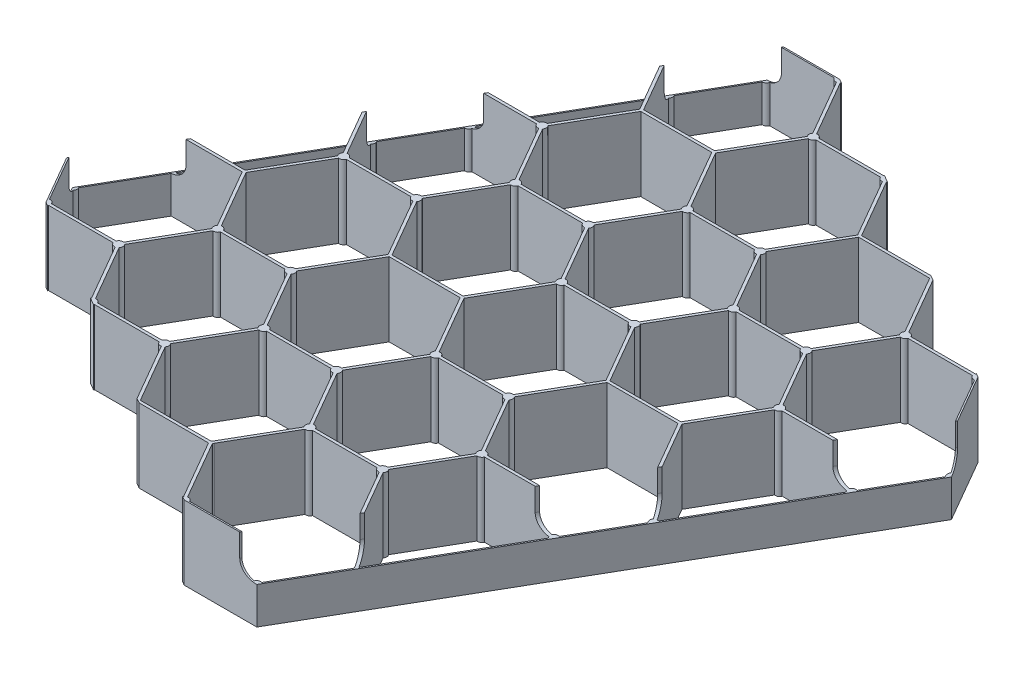
SolidWorks part; units mm, degrees
ref_plane "Front Plane" through (0, 0, 0) normal (0, 0, 1) x (1, 0, 0)
ref_plane "Top Plane" through (0, 0, 0) normal (0, 1, 0) x (1, 0, 0)
ref_plane "Right Plane" through (0, 0, 0) normal (1, 0, 0) x (0, 0, -1)
sketch "Sketch2" plane through (0, 0, 0) normal (0, 1, 0) x (1, 0, 0)
  line L120 (178.2915, 45.6003) -> (166.2528, 66.4519)
  line L121 (167.0028, 23.4497) -> (178.2915, 43.0022)
  line L122 (178.2915, 1.299) -> (167.0028, 20.8516)
  line L124 (166.2528, -22.1506) -> (178.2915, -1.299)
  line L127 (-12.7887, -22.1506) -> (166.2528, -22.1506)
  line L128 (164.8386, 21.6506) -> (142.0896, 21.6506)
  line L130 (177.9013, 0.9747) -> (166.5269, 20.6759)
  line L132 (165.9641, -21.6506) -> (177.9013, -0.9747)
  line L136 (140.9641, -21.6506) -> (165.9641, -21.6506)
  line L139 (129.0269, -0.9747) -> (140.9641, -21.6506)
  line L145 (140.4013, 20.6759) -> (129.0269, 0.9747)
  line L146 (142.0896, 22.6506) -> (164.8386, 22.6506)
  line L147 (129.0269, 43.3265) -> (140.4013, 23.6254)
  line L148 (140.9641, 65.9519) -> (129.0269, 45.276)
  line L149 (165.9641, 65.9519) -> (140.9641, 65.9519)
  line L150 (177.9013, 45.276) -> (165.9641, 65.9519)
  line L154 (178.2915, 87.3035) -> (166.2528, 66.4519)
  line L155 (101.1693, 87.6278) -> (89.2321, 66.9519)
  line L156 (89.7948, 109.2784) -> (101.1693, 89.5773)
  line L157 (65.3576, 110.2532) -> (88.1065, 110.2532)
  line L158 (52.2948, 89.5773) -> (63.6693, 109.2784)
  line L159 (63.9368, 67.4633) -> (52.2948, 87.6278)
  line L160 (89.2321, 66.9519) -> (64.2321, 66.9519)
  line L162 (102.0353, 87.1278) -> (90.3868, 66.9519)
  line L163 (126.4725, 88.1025) -> (103.7236, 88.1025)
  line L164 (139.8094, 66.9519) -> (128.1608, 87.1278)
  line L165 (167.0028, 109.4541) -> (178.2915, 89.9016)
  line L166 (177.9013, 87.6278) -> (165.9641, 66.9519)
  line L167 (166.5269, 109.2784) -> (177.9013, 89.5773)
  line L168 (142.0896, 110.2532) -> (164.8386, 110.2532)
  line L169 (129.0269, 89.5773) -> (140.4013, 109.2784)
  line L170 (140.9641, 66.9519) -> (129.0269, 87.6278)
  line L171 (165.9641, 66.9519) -> (140.9641, 66.9519)
  line L172 (178.2915, 131.6048) -> (167.0028, 112.0522)
  line L173 (166.2528, 155.0544) -> (178.2915, 134.2028)
  line L174 (90.6608, 109.7784) -> (102.0353, 90.0773)
  line L177 (139.5353, 111.7279) -> (128.1608, 131.4291)
  line L178 (128.1608, 90.0773) -> (139.5353, 109.7784)
  line L179 (103.7236, 89.1025) -> (126.4725, 89.1025)
  line L180 (140.9641, 154.5544) -> (165.9641, 154.5544)
  line L181 (129.0269, 133.8786) -> (140.9641, 154.5544)
  line L182 (140.4013, 112.2279) -> (129.0269, 131.9291)
  line L183 (164.8386, 111.2532) -> (142.0896, 111.2532)
  line L184 (177.9013, 131.9291) -> (166.5269, 112.2279)
  line L185 (165.9641, 154.5544) -> (177.9013, 133.8786)
  line L187 (90.0981, 155.0544) -> (102.0353, 134.3786)
  line L189 (128.1608, 134.3786) -> (140.0981, 155.0544)
  line L190 (64.2321, 154.5544) -> (89.2321, 154.5544)
  line L191 (52.2948, 133.8786) -> (64.2321, 154.5544)
  line L192 (63.6693, 112.2279) -> (52.2948, 131.9291)
  line L193 (88.1065, 111.2532) -> (65.3576, 111.2532)
  line L194 (101.1693, 131.9291) -> (89.7948, 112.2279)
  line L195 (89.2321, 154.5544) -> (101.1693, 133.8786)
  line L198 (51.4288, 134.3786) -> (63.366, 155.0544)
  line L199 (26.9916, 133.4038) -> (49.7405, 133.4038)
  line L200 (13.366, 155.0544) -> (25.3033, 134.3786)
  line L203 (-13.0628, 112.2279) -> (-24.4372, 131.9291)
  line L204 (11.3745, 111.2532) -> (-11.3745, 111.2532)
  line L205 (24.4372, 131.9291) -> (13.0628, 112.2279)
  line L206 (12.5, 154.5544) -> (24.4372, 133.8786)
  line L207 (-12.5, 154.5544) -> (12.5, 154.5544)
  line L208 (-24.4372, 133.8786) -> (-12.5, 154.5544)
  line L209 (13.9288, 109.7784) -> (25.3033, 90.0773)
  line L210 (25.3033, 131.4291) -> (13.9288, 111.7279)
  line L211 (49.7405, 132.4038) -> (26.9916, 132.4038)
  line L212 (62.8033, 111.7279) -> (51.4288, 131.4291)
  line L213 (51.4288, 90.0773) -> (62.8033, 109.7784)
  line L214 (26.9916, 89.1025) -> (49.7405, 89.1025)
  line L216 (51.4288, 87.1278) -> (63.0774, 66.9519)
  line L217 (26.9916, 88.1025) -> (49.7405, 88.1025)
  line L218 (13.6547, 66.9519) -> (25.3033, 87.1278)
  line L220 (-13.0628, 109.2784) -> (-24.4372, 89.5773)
  line L221 (11.3745, 110.2532) -> (-11.3745, 110.2532)
  line L222 (24.4372, 89.5773) -> (13.0628, 109.2784)
  line L223 (12.5, 66.9519) -> (24.4372, 87.6278)
  line L224 (-12.5, 66.9519) -> (12.5, 66.9519)
  line L225 (-24.4372, 87.6278) -> (-12.5, 66.9519)
  line L228 (166.5269, 23.6254) -> (177.9013, 43.3265)
  line L255 (-13.0628, 289.433) -> (-24.4372, 309.1341)
  line L257 (139.8094, 65.9519) -> (128.1608, 45.776)
  line L259 (102.0353, 45.776) -> (90.3868, 65.9519)
  line L260 (126.4725, 44.8013) -> (103.7236, 44.8013)
  line L261 (13.6547, 65.9519) -> (25.3033, 45.776)
  line L263 (51.4288, 45.776) -> (63.0774, 65.9519)
  line L264 (26.9916, 44.8013) -> (49.7405, 44.8013)
  line L265 (12.5, 65.9519) -> (24.4372, 45.276)
  line L266 (-12.5, 65.9519) -> (12.5, 65.9519)
  line L267 (-24.4372, 45.276) -> (-12.5, 65.9519)
  line L268 (-13.0628, 23.6254) -> (-24.4372, 43.3265)
  line L269 (11.3745, 22.6506) -> (-11.3745, 22.6506)
  line L270 (24.4372, 43.3265) -> (13.0628, 23.6254)
  line L271 (90.3868, -21.6506) -> (102.0353, -1.4747)
  line L272 (90.3868, -21.6506) -> (139.8094, -21.6506)
  line L273 (128.1608, -1.4747) -> (139.8094, -21.6506)
  line L274 (103.7236, -0.5) -> (126.4725, -0.5)
  line L275 (103.7236, 43.8013) -> (126.4725, 43.8013)
  line L276 (90.6608, 23.1254) -> (102.0353, 42.8265)
  line L277 (102.0353, 1.4747) -> (90.6608, 21.1759)
  line L278 (126.4725, 0.5) -> (103.7236, 0.5)
  line L279 (139.5353, 21.1759) -> (128.1608, 1.4747)
  line L280 (128.1608, 42.8265) -> (139.5353, 23.1254)
  line L281 (65.3576, 22.6506) -> (88.1065, 22.6506)
  line L282 (52.2948, 43.3265) -> (63.6693, 23.6254)
  line L283 (64.2321, 65.9519) -> (52.2948, 45.276)
  line L284 (89.2321, 65.9519) -> (64.2321, 65.9519)
  line L285 (101.1693, 45.276) -> (89.2321, 65.9519)
  line L286 (89.7948, 23.6254) -> (101.1693, 43.3265)
  line L287 (88.1065, 21.6506) -> (65.3576, 21.6506)
  line L288 (101.1693, 0.9747) -> (89.7948, 20.6759)
  line L289 (89.2321, -21.6506) -> (101.1693, -0.9747)
  line L290 (64.2321, -21.6506) -> (89.2321, -21.6506)
  line L291 (52.2948, -0.9747) -> (64.2321, -21.6506)
  line L292 (63.6693, 20.6759) -> (52.2948, 0.9747)
  line L293 (13.9288, 23.1254) -> (25.3033, 42.8265)
  line L294 (25.3033, 1.4747) -> (13.9288, 21.1759)
  line L295 (49.7405, 0.5) -> (26.9916, 0.5)
  line L296 (62.8033, 21.1759) -> (51.4288, 1.4747)
  line L297 (51.4288, 42.8265) -> (62.8033, 23.1254)
  line L298 (26.9916, 43.8013) -> (49.7405, 43.8013)
  line L299 (13.6547, -21.6506) -> (25.3033, -1.4747)
  line L300 (13.6547, -21.6506) -> (63.0774, -21.6506)
  line L301 (51.4288, -1.4747) -> (63.0774, -21.6506)
  line L302 (26.9916, -0.5) -> (49.7405, -0.5)
  line L303 (11.3745, 21.6506) -> (-11.3745, 21.6506)
  line L304 (24.4372, 0.9747) -> (13.0628, 20.6759)
  line L305 (12.5, -21.6506) -> (24.4372, -0.9747)
  line L306 (-12.5, -21.6506) -> (12.5, -21.6506)
  line L307 (-24.4372, -0.9747) -> (-12.5, -21.6506)
  line L308 (-13.0628, 20.6759) -> (-24.4372, 0.9747)
  line L309 (-24.4372, 311.0836) -> (-12.5, 331.7595)
  line L310 (-12.5, 331.7595) -> (12.5, 331.7595)
  line L311 (12.5, 331.7595) -> (24.4372, 311.0836)
  line L312 (24.4372, 309.1341) -> (13.0628, 289.433)
  line L313 (11.3745, 288.4583) -> (-11.3745, 288.4583)
  line L314 (26.9916, 310.6089) -> (49.7405, 310.6089)
  line L315 (51.4288, 311.5836) -> (63.0774, 331.7595)
  line L316 (13.6547, 331.7595) -> (63.0774, 331.7595)
  line L317 (13.6547, 331.7595) -> (25.3033, 311.5836)
  line L318 (26.9916, 266.3076) -> (49.7405, 266.3076)
  line L319 (51.4288, 267.2824) -> (62.8033, 286.9835)
  line L320 (62.8033, 288.933) -> (51.4288, 308.6341)
  line L321 (49.7405, 309.6089) -> (26.9916, 309.6089)
  line L322 (25.3033, 308.6341) -> (13.9288, 288.933)
  line L323 (13.9288, 286.9835) -> (25.3033, 267.2824)
  line L324 (63.6693, 289.433) -> (52.2948, 309.1341)
  line L325 (52.2948, 311.0836) -> (64.2321, 331.7595)
  line L326 (64.2321, 331.7595) -> (89.2321, 331.7595)
  line L327 (89.2321, 331.7595) -> (101.1693, 311.0836)
  line L328 (101.1693, 309.1341) -> (89.7948, 289.433)
  line L329 (88.1065, 288.4583) -> (65.3576, 288.4583)
  line L330 (89.7948, 286.4835) -> (101.1693, 266.7824)
  line L331 (101.1693, 264.8329) -> (89.2321, 244.157)
  line L332 (89.2321, 244.157) -> (64.2321, 244.157)
  line L333 (64.2321, 244.157) -> (52.2948, 264.8329)
  line L334 (52.2948, 266.7824) -> (63.6693, 286.4835)
  line L335 (65.3576, 287.4583) -> (88.1065, 287.4583)
  line L336 (128.1608, 267.2824) -> (139.5353, 286.9835)
  line L337 (139.5353, 288.933) -> (128.1608, 308.6341)
  line L338 (126.4725, 309.6089) -> (103.7236, 309.6089)
  line L339 (102.0353, 308.6341) -> (90.6608, 288.933)
  line L340 (90.6608, 286.9835) -> (102.0353, 267.2824)
  line L341 (103.7236, 266.3076) -> (126.4725, 266.3076)
  line L342 (103.7236, 310.6089) -> (126.4725, 310.6089)
  line L343 (128.1608, 311.5836) -> (139.8094, 331.7595)
  line L344 (90.3868, 331.7595) -> (139.8094, 331.7595)
  line L345 (90.3868, 331.7595) -> (102.0353, 311.5836)
  line L346 (24.4372, 266.7824) -> (13.0628, 286.4835)
  line L347 (11.3745, 287.4583) -> (-11.3745, 287.4583)
  line L348 (-13.0628, 286.4835) -> (-24.4372, 266.7824)
  line L349 (-24.4372, 264.8329) -> (-12.5, 244.157)
  line L350 (-12.5, 244.157) -> (12.5, 244.157)
  line L351 (12.5, 244.157) -> (24.4372, 264.8329)
  line L352 (26.9916, 265.3076) -> (49.7405, 265.3076)
  line L353 (51.4288, 264.3329) -> (63.366, 243.657)
  line L355 (13.366, 243.657) -> (25.3033, 264.3329)
  line L356 (126.4725, 265.3076) -> (103.7236, 265.3076)
  line L357 (102.0353, 264.3329) -> (90.0981, 243.657)
  line L359 (140.0981, 243.657) -> (128.1608, 264.3329)
  line L360 (166.5269, 286.4835) -> (177.9013, 266.7824)
  line L362 (-24.4372, 222.4811) -> (-12.5, 243.157)
  line L363 (-12.5, 243.157) -> (12.5, 243.157)
  line L364 (12.5, 243.157) -> (24.4372, 222.4811)
  line L365 (24.4372, 220.5316) -> (13.0628, 200.8305)
  line L366 (11.3745, 199.8557) -> (-11.3745, 199.8557)
  line L367 (-13.0628, 200.8305) -> (-24.4372, 220.5316)
  line L369 (13.366, 243.657) -> (25.3033, 222.9811)
  line L370 (26.9916, 222.0064) -> (49.7405, 222.0064)
  line L371 (51.4288, 222.9811) -> (63.366, 243.657)
  line L373 (26.9916, 221.0064) -> (49.7405, 221.0064)
  line L374 (51.4288, 220.0316) -> (62.8033, 200.3305)
  line L375 (62.8033, 198.381) -> (51.4288, 178.6798)
  line L376 (49.7405, 177.7051) -> (26.9916, 177.7051)
  line L377 (25.3033, 178.6798) -> (13.9288, 198.381)
  line L378 (13.9288, 200.3305) -> (25.3033, 220.0316)
  line L379 (-24.4372, 176.2303) -> (-12.5, 155.5544)
  line L380 (-12.5, 155.5544) -> (12.5, 155.5544)
  line L381 (12.5, 155.5544) -> (24.4372, 176.2303)
  line L382 (24.4372, 178.1798) -> (13.0628, 197.881)
  line L383 (11.3745, 198.8557) -> (-11.3745, 198.8557)
  line L384 (-13.0628, 197.881) -> (-24.4372, 178.1798)
  line L387 (13.366, 155.0544) -> (25.3033, 175.7303)
  line L388 (26.9916, 176.7051) -> (49.7405, 176.7051)
  line L389 (51.4288, 175.7303) -> (63.366, 155.0544)
  line L391 (89.2321, 155.5544) -> (101.1693, 176.2303)
  line L392 (101.1693, 178.1798) -> (89.7948, 197.881)
  line L393 (88.1065, 198.8557) -> (65.3576, 198.8557)
  line L394 (63.6693, 197.881) -> (52.2948, 178.1798)
  line L395 (52.2948, 176.2303) -> (64.2321, 155.5544)
  line L396 (64.2321, 155.5544) -> (89.2321, 155.5544)
  line L397 (128.1608, 175.7303) -> (140.0981, 155.0544)
  line L399 (90.0981, 155.0544) -> (102.0353, 175.7303)
  line L400 (103.7236, 176.7051) -> (126.4725, 176.7051)
  line L401 (165.9641, 155.5544) -> (177.9013, 176.2303)
  line L402 (177.9013, 178.1798) -> (166.5269, 197.881)
  line L403 (164.8386, 198.8557) -> (142.0896, 198.8557)
  line L404 (140.4013, 197.881) -> (129.0269, 178.1798)
  line L405 (129.0269, 176.2303) -> (140.9641, 155.5544)
  line L406 (140.9641, 155.5544) -> (165.9641, 155.5544)
  line L407 (103.7236, 221.0064) -> (126.4725, 221.0064)
  line L408 (128.1608, 220.0316) -> (139.5353, 200.3305)
  line L409 (139.5353, 198.381) -> (128.1608, 178.6798)
  line L410 (126.4725, 177.7051) -> (103.7236, 177.7051)
  line L411 (102.0353, 178.6798) -> (90.6608, 198.381)
  line L412 (90.6608, 200.3305) -> (102.0353, 220.0316)
  line L413 (166.2528, 155.0544) -> (178.2915, 175.906)
  line L414 (178.2915, 178.5041) -> (167.0028, 198.0567)
  line L415 (165.9641, 243.157) -> (140.9641, 243.157)
  line L416 (140.9641, 243.157) -> (129.0269, 222.4811)
  line L417 (129.0269, 220.5316) -> (140.4013, 200.8305)
  line L418 (142.0896, 199.8557) -> (164.8386, 199.8557)
  line L419 (166.5269, 200.8305) -> (177.9013, 220.5316)
  line L420 (177.9013, 222.4811) -> (165.9641, 243.157)
  line L421 (167.0028, 200.6548) -> (178.2915, 220.2073)
  line L422 (140.0981, 243.657) -> (128.1608, 222.9811)
  line L423 (126.4725, 222.0064) -> (103.7236, 222.0064)
  line L424 (102.0353, 222.9811) -> (90.0981, 243.657)
  line L426 (89.2321, 243.157) -> (64.2321, 243.157)
  line L427 (64.2321, 243.157) -> (52.2948, 222.4811)
  line L428 (52.2948, 220.5316) -> (63.6693, 200.8305)
  line L429 (65.3576, 199.8557) -> (88.1065, 199.8557)
  line L430 (89.7948, 200.8305) -> (101.1693, 220.5316)
  line L431 (101.1693, 222.4811) -> (89.2321, 243.157)
  line L432 (178.2915, 222.8054) -> (166.2528, 243.657)
  line L433 (177.9013, 264.8329) -> (165.9641, 244.157)
  line L434 (165.9641, 244.157) -> (140.9641, 244.157)
  line L435 (140.9641, 244.157) -> (129.0269, 264.8329)
  line L436 (129.0269, 266.7824) -> (140.4013, 286.4835)
  line L437 (142.0896, 287.4583) -> (164.8386, 287.4583)
  line L438 (140.4013, 289.433) -> (129.0269, 309.1341)
  line L439 (129.0269, 311.0836) -> (140.9641, 331.7595)
  line L440 (140.9641, 331.7595) -> (165.9641, 331.7595)
  line L441 (165.9641, 331.7595) -> (177.9013, 311.0836)
  line L442 (177.9013, 309.1341) -> (166.5269, 289.433)
  line L443 (164.8386, 288.4583) -> (142.0896, 288.4583)
  line L444 (-12.7887, 332.2595) -> (166.2528, 332.2595)
  line L445 (166.2528, 332.2595) -> (178.2915, 311.4079)
  line L446 (178.2915, 308.8099) -> (167.0028, 289.2573)
  line L447 (167.0028, 286.6592) -> (178.2915, 267.1067)
  line L448 (178.2915, 264.5086) -> (166.2528, 243.657)
  line L453 (13.6547, 66.9519) -> (13.3794, 66.4519)
  line L454 (13.3794, 66.4519) -> (13.6547, 65.9519)
  line L455 (63.0774, 66.9519) -> (63.3527, 66.4519)
  line L456 (63.3527, 66.4519) -> (63.0774, 65.9519)
  line L457 (90.3868, 66.9519) -> (90.0981, 66.4519)
  line L458 (90.0981, 66.4519) -> (90.3868, 65.9519)
  line L459 (139.8094, 66.9519) -> (140.0981, 66.4519)
  line L460 (140.0981, 66.4519) -> (139.8094, 65.9519)
  line L461 (-13.366, 155.0544) -> (-13.6547, 154.5544)
  line L462 (13.6547, 155.5544) -> (13.366, 155.0544)
  line L463 (13.366, 155.0544) -> (13.6547, 154.5544)
  line L464 (0, 357.2689) -> (0, 393.9741)
  line L465 (-13.6547, 155.5544) -> (-13.366, 155.0544)
  line L466 (-140.0981, 66.4519) -> (-139.8094, 65.9519)
  line L467 (-139.8094, 66.9519) -> (-140.0981, 66.4519)
  line L468 (-90.0981, 66.4519) -> (-90.3868, 65.9519)
  line L469 (-90.3868, 66.9519) -> (-90.0981, 66.4519)
  line L470 (-63.3527, 66.4519) -> (-63.0774, 65.9519)
  line L471 (-63.0774, 66.9519) -> (-63.3527, 66.4519)
  line L472 (-13.3794, 66.4519) -> (-13.6547, 65.9519)
  line L473 (-13.6547, 66.9519) -> (-13.3794, 66.4519)
  line L478 (-178.2915, 264.5086) -> (-166.2528, 243.657)
  line L479 (-167.0028, 286.6592) -> (-178.2915, 267.1067)
  line L480 (-178.2915, 308.8099) -> (-167.0028, 289.2573)
  line L481 (-166.2528, 332.2595) -> (-178.2915, 311.4079)
  line L482 (12.7887, 332.2595) -> (-166.2528, 332.2595)
  line L483 (-164.8386, 288.4583) -> (-142.0896, 288.4583)
  line L484 (-177.9013, 309.1341) -> (-166.5269, 289.433)
  line L485 (-165.9641, 331.7595) -> (-177.9013, 311.0836)
  line L486 (-140.9641, 331.7595) -> (-165.9641, 331.7595)
  line L487 (-129.0269, 311.0836) -> (-140.9641, 331.7595)
  line L488 (-140.4013, 289.433) -> (-129.0269, 309.1341)
  line L489 (-142.0896, 287.4583) -> (-164.8386, 287.4583)
  line L490 (-129.0269, 266.7824) -> (-140.4013, 286.4835)
  line L491 (-140.9641, 244.157) -> (-129.0269, 264.8329)
  line L492 (-165.9641, 244.157) -> (-140.9641, 244.157)
  line L493 (-177.9013, 264.8329) -> (-165.9641, 244.157)
  line L494 (-178.2915, 222.8054) -> (-166.2528, 243.657)
  line L495 (-101.1693, 222.4811) -> (-89.2321, 243.157)
  line L496 (-89.7948, 200.8305) -> (-101.1693, 220.5316)
  line L497 (-65.3576, 199.8557) -> (-88.1065, 199.8557)
  line L498 (-52.2948, 220.5316) -> (-63.6693, 200.8305)
  line L499 (-64.2321, 243.157) -> (-52.2948, 222.4811)
  line L500 (-89.2321, 243.157) -> (-64.2321, 243.157)
  line L501 (-102.0353, 222.9811) -> (-90.0981, 243.657)
  line L502 (-126.4725, 222.0064) -> (-103.7236, 222.0064)
  line L503 (-140.0981, 243.657) -> (-128.1608, 222.9811)
  line L504 (-167.0028, 200.6548) -> (-178.2915, 220.2073)
  line L505 (-177.9013, 222.4811) -> (-165.9641, 243.157)
  line L506 (-166.5269, 200.8305) -> (-177.9013, 220.5316)
  line L507 (-142.0896, 199.8557) -> (-164.8386, 199.8557)
  line L508 (-129.0269, 220.5316) -> (-140.4013, 200.8305)
  line L509 (-140.9641, 243.157) -> (-129.0269, 222.4811)
  line L510 (-165.9641, 243.157) -> (-140.9641, 243.157)
  line L511 (-178.2915, 178.5041) -> (-167.0028, 198.0567)
  line L512 (-166.2528, 155.0544) -> (-178.2915, 175.906)
  line L513 (-90.6608, 200.3305) -> (-102.0353, 220.0316)
  line L514 (-102.0353, 178.6798) -> (-90.6608, 198.381)
  line L515 (-126.4725, 177.7051) -> (-103.7236, 177.7051)
  line L516 (-139.5353, 198.381) -> (-128.1608, 178.6798)
  line L517 (-128.1608, 220.0316) -> (-139.5353, 200.3305)
  line L518 (-103.7236, 221.0064) -> (-126.4725, 221.0064)
  line L519 (-140.9641, 155.5544) -> (-165.9641, 155.5544)
  line L520 (-129.0269, 176.2303) -> (-140.9641, 155.5544)
  line L521 (-140.4013, 197.881) -> (-129.0269, 178.1798)
  line L522 (-164.8386, 198.8557) -> (-142.0896, 198.8557)
  line L523 (-177.9013, 178.1798) -> (-166.5269, 197.881)
  line L524 (-165.9641, 155.5544) -> (-177.9013, 176.2303)
  line L525 (-103.7236, 176.7051) -> (-126.4725, 176.7051)
  line L526 (-90.0981, 155.0544) -> (-102.0353, 175.7303)
  line L527 (-128.1608, 175.7303) -> (-140.0981, 155.0544)
  line L528 (-64.2321, 155.5544) -> (-88.6547, 155.5544)
  line L529 (-52.2948, 176.2303) -> (-64.2321, 155.5544)
  line L530 (-63.6693, 197.881) -> (-52.2948, 178.1798)
  line L531 (-88.1065, 198.8557) -> (-65.3576, 198.8557)
  line L532 (-101.1693, 178.1798) -> (-89.7948, 197.881)
  line L533 (-89.2321, 155.5544) -> (-101.1693, 176.2303)
  line L534 (-51.4288, 175.7303) -> (-63.366, 155.0544)
  line L535 (-26.9916, 176.7051) -> (-49.7405, 176.7051)
  line L536 (-13.366, 155.0544) -> (-25.3033, 175.7303)
  line L539 (13.0628, 197.881) -> (24.4372, 178.1798)
  line L540 (-24.4372, 178.1798) -> (-13.0628, 197.881)
  line L541 (-12.5, 155.5544) -> (-24.4372, 176.2303)
  line L542 (24.4372, 176.2303) -> (12.5, 155.5544)
  line L543 (-13.9288, 200.3305) -> (-25.3033, 220.0316)
  line L544 (-25.3033, 178.6798) -> (-13.9288, 198.381)
  line L545 (-49.7405, 177.7051) -> (-26.9916, 177.7051)
  line L546 (-62.8033, 198.381) -> (-51.4288, 178.6798)
  line L547 (-51.4288, 220.0316) -> (-62.8033, 200.3305)
  line L548 (-26.9916, 221.0064) -> (-49.7405, 221.0064)
  line L549 (-51.4288, 222.9811) -> (-63.366, 243.657)
  line L550 (-26.9916, 222.0064) -> (-49.7405, 222.0064)
  line L551 (-13.366, 243.657) -> (-25.3033, 222.9811)
  line L553 (13.0628, 200.8305) -> (24.4372, 220.5316)
  line L554 (-24.4372, 220.5316) -> (-13.0628, 200.8305)
  line L555 (-12.5, 243.157) -> (-24.4372, 222.4811)
  line L556 (24.4372, 222.4811) -> (12.5, 243.157)
  line L558 (-166.5269, 286.4835) -> (-177.9013, 266.7824)
  line L559 (-140.0981, 243.657) -> (-128.1608, 264.3329)
  line L560 (-102.0353, 264.3329) -> (-90.0981, 243.657)
  line L561 (-126.4725, 265.3076) -> (-103.7236, 265.3076)
  line L562 (-13.366, 243.657) -> (-25.3033, 264.3329)
  line L563 (-51.4288, 264.3329) -> (-63.366, 243.657)
  line L564 (-26.9916, 265.3076) -> (-49.7405, 265.3076)
  line L565 (-12.5, 244.157) -> (-24.4372, 264.8329)
  line L566 (24.4372, 264.8329) -> (12.5, 244.157)
  line L567 (13.0628, 286.4835) -> (24.4372, 266.7824)
  line L568 (-24.4372, 266.7824) -> (-13.0628, 286.4835)
  line L569 (-90.3868, 331.7595) -> (-102.0353, 311.5836)
  line L570 (-90.3868, 331.7595) -> (-139.8094, 331.7595)
  line L571 (-128.1608, 311.5836) -> (-139.8094, 331.7595)
  line L572 (-103.7236, 310.6089) -> (-126.4725, 310.6089)
  line L573 (-103.7236, 266.3076) -> (-126.4725, 266.3076)
  line L574 (-90.6608, 286.9835) -> (-102.0353, 267.2824)
  line L575 (-102.0353, 308.6341) -> (-90.6608, 288.933)
  line L576 (-126.4725, 309.6089) -> (-103.7236, 309.6089)
  line L577 (-139.5353, 288.933) -> (-128.1608, 308.6341)
  line L578 (-128.1608, 267.2824) -> (-139.5353, 286.9835)
  line L579 (-65.3576, 287.4583) -> (-88.1065, 287.4583)
  line L580 (-52.2948, 266.7824) -> (-63.6693, 286.4835)
  line L581 (-64.2321, 244.157) -> (-52.2948, 264.8329)
  line L582 (-89.2321, 244.157) -> (-64.2321, 244.157)
  line L583 (-101.1693, 264.8329) -> (-89.2321, 244.157)
  line L584 (-89.7948, 286.4835) -> (-101.1693, 266.7824)
  line L585 (-88.1065, 288.4583) -> (-65.3576, 288.4583)
  line L586 (-101.1693, 309.1341) -> (-89.7948, 289.433)
  line L587 (-89.2321, 331.7595) -> (-101.1693, 311.0836)
  line L588 (-64.2321, 331.7595) -> (-89.2321, 331.7595)
  line L589 (-52.2948, 311.0836) -> (-64.2321, 331.7595)
  line L590 (-63.6693, 289.433) -> (-52.2948, 309.1341)
  line L591 (-13.9288, 286.9835) -> (-25.3033, 267.2824)
  line L592 (-25.3033, 308.6341) -> (-13.9288, 288.933)
  line L593 (-49.7405, 309.6089) -> (-26.9916, 309.6089)
  line L594 (-62.8033, 288.933) -> (-51.4288, 308.6341)
  line L595 (-51.4288, 267.2824) -> (-62.8033, 286.9835)
  line L596 (-26.9916, 266.3076) -> (-49.7405, 266.3076)
  line L597 (-13.6547, 331.7595) -> (-25.3033, 311.5836)
  line L598 (-13.6547, 331.7595) -> (-63.0774, 331.7595)
  line L599 (-51.4288, 311.5836) -> (-63.0774, 331.7595)
  line L600 (-26.9916, 310.6089) -> (-49.7405, 310.6089)
  line L601 (-24.4372, 309.1341) -> (-13.0628, 289.433)
  line L602 (-12.5, 331.7595) -> (-24.4372, 311.0836)
  line L603 (24.4372, 311.0836) -> (12.5, 331.7595)
  line L604 (13.0628, 20.6759) -> (24.4372, 0.9747)
  line L605 (24.4372, -0.9747) -> (12.5, -21.6506)
  line L606 (-12.5, -21.6506) -> (-24.4372, -0.9747)
  line L607 (-24.4372, 0.9747) -> (-13.0628, 20.6759)
  line L608 (-26.9916, -0.5) -> (-49.7405, -0.5)
  line L609 (-51.4288, -1.4747) -> (-63.0774, -21.6506)
  line L610 (-13.6547, -21.6506) -> (-63.0774, -21.6506)
  line L611 (-13.6547, -21.6506) -> (-25.3033, -1.4747)
  line L612 (-26.9916, 43.8013) -> (-49.7405, 43.8013)
  line L613 (-51.4288, 42.8265) -> (-62.8033, 23.1254)
  line L614 (-62.8033, 21.1759) -> (-51.4288, 1.4747)
  line L615 (-49.7405, 0.5) -> (-26.9916, 0.5)
  line L616 (-25.3033, 1.4747) -> (-13.9288, 21.1759)
  line L617 (-13.9288, 23.1254) -> (-25.3033, 42.8265)
  line L618 (-63.6693, 20.6759) -> (-52.2948, 0.9747)
  line L619 (-52.2948, -0.9747) -> (-64.2321, -21.6506)
  line L620 (-64.2321, -21.6506) -> (-89.2321, -21.6506)
  line L621 (-89.2321, -21.6506) -> (-101.1693, -0.9747)
  line L622 (-101.1693, 0.9747) -> (-89.7948, 20.6759)
  line L623 (-88.1065, 21.6506) -> (-65.3576, 21.6506)
  line L624 (-89.7948, 23.6254) -> (-101.1693, 43.3265)
  line L625 (-101.1693, 45.276) -> (-89.2321, 65.9519)
  line L626 (-89.2321, 65.9519) -> (-64.2321, 65.9519)
  line L627 (-64.2321, 65.9519) -> (-52.2948, 45.276)
  line L628 (-52.2948, 43.3265) -> (-63.6693, 23.6254)
  line L629 (-65.3576, 22.6506) -> (-88.1065, 22.6506)
  line L630 (-128.1608, 42.8265) -> (-139.5353, 23.1254)
  line L631 (-139.5353, 21.1759) -> (-128.1608, 1.4747)
  line L632 (-126.4725, 0.5) -> (-103.7236, 0.5)
  line L633 (-102.0353, 1.4747) -> (-90.6608, 21.1759)
  line L634 (-90.6608, 23.1254) -> (-102.0353, 42.8265)
  line L635 (-103.7236, 43.8013) -> (-126.4725, 43.8013)
  line L636 (-103.7236, -0.5) -> (-126.4725, -0.5)
  line L637 (-128.1608, -1.4747) -> (-139.8094, -21.6506)
  line L638 (-90.3868, -21.6506) -> (-139.8094, -21.6506)
  line L639 (-90.3868, -21.6506) -> (-102.0353, -1.4747)
  line L640 (-24.4372, 43.3265) -> (-13.0628, 23.6254)
  line L641 (13.0628, 23.6254) -> (24.4372, 43.3265)
  line L642 (24.4372, 45.276) -> (12.5, 65.9519)
  line L643 (-12.5, 65.9519) -> (-24.4372, 45.276)
  line L644 (-26.9916, 44.8013) -> (-49.7405, 44.8013)
  line L645 (-51.4288, 45.776) -> (-63.0774, 65.9519)
  line L646 (-13.6547, 65.9519) -> (-25.3033, 45.776)
  line L647 (-126.4725, 44.8013) -> (-103.7236, 44.8013)
  line L648 (-102.0353, 45.776) -> (-90.3868, 65.9519)
  line L649 (-139.8094, 65.9519) -> (-128.1608, 45.776)
  line L650 (13.0628, 289.433) -> (24.4372, 309.1341)
  line L651 (-166.5269, 23.6254) -> (-177.9013, 43.3265)
  line L653 (24.4372, 87.6278) -> (12.5, 66.9519)
  line L654 (-12.5, 66.9519) -> (-24.4372, 87.6278)
  line L655 (-24.4372, 89.5773) -> (-13.0628, 109.2784)
  line L656 (13.0628, 109.2784) -> (24.4372, 89.5773)
  line L658 (-13.6547, 66.9519) -> (-25.3033, 87.1278)
  line L659 (-26.9916, 88.1025) -> (-49.7405, 88.1025)
  line L660 (-51.4288, 87.1278) -> (-63.0774, 66.9519)
  line L661 (-26.9916, 89.1025) -> (-49.7405, 89.1025)
  line L662 (-51.4288, 90.0773) -> (-62.8033, 109.7784)
  line L663 (-62.8033, 111.7279) -> (-51.4288, 131.4291)
  line L664 (-49.7405, 132.4038) -> (-26.9916, 132.4038)
  line L665 (-25.3033, 131.4291) -> (-13.9288, 111.7279)
  line L666 (-13.9288, 109.7784) -> (-25.3033, 90.0773)
  line L667 (24.4372, 133.8786) -> (12.5, 154.5544)
  line L668 (-12.5, 154.5544) -> (-24.4372, 133.8786)
  line L669 (-24.4372, 131.9291) -> (-13.0628, 112.2279)
  line L670 (13.0628, 112.2279) -> (24.4372, 131.9291)
  line L673 (-13.366, 155.0544) -> (-25.3033, 134.3786)
  line L674 (-26.9916, 133.4038) -> (-49.7405, 133.4038)
  line L675 (-51.4288, 134.3786) -> (-63.366, 155.0544)
  line L676 (-89.2321, 154.5544) -> (-101.1693, 133.8786)
  line L677 (-101.1693, 131.9291) -> (-89.7948, 112.2279)
  line L678 (-88.1065, 111.2532) -> (-65.3576, 111.2532)
  line L679 (-63.6693, 112.2279) -> (-52.2948, 131.9291)
  line L680 (-52.2948, 133.8786) -> (-64.2321, 154.5544)
  line L681 (-64.2321, 154.5544) -> (-89.2321, 154.5544)
  line L682 (-128.1608, 134.3786) -> (-140.0981, 155.0544)
  line L683 (-90.0981, 155.0544) -> (-102.0353, 134.3786)
  line L684 (-103.7236, 133.4038) -> (-126.4725, 133.4038)
  line L685 (-165.9641, 154.5544) -> (-177.9013, 133.8786)
  line L686 (-177.9013, 131.9291) -> (-166.5269, 112.2279)
  line L687 (-164.8386, 111.2532) -> (-142.0896, 111.2532)
  line L688 (-140.4013, 112.2279) -> (-129.0269, 131.9291)
  line L689 (-129.0269, 133.8786) -> (-140.9641, 154.5544)
  line L690 (-140.9641, 154.5544) -> (-165.9641, 154.5544)
  line L691 (-103.7236, 89.1025) -> (-126.4725, 89.1025)
  line L692 (-128.1608, 90.0773) -> (-139.5353, 109.7784)
  line L693 (-139.5353, 111.7279) -> (-128.1608, 131.4291)
  line L694 (-126.4725, 132.4038) -> (-103.7236, 132.4038)
  line L695 (-102.0353, 131.4291) -> (-90.6608, 111.7279)
  line L696 (-90.6608, 109.7784) -> (-102.0353, 90.0773)
  line L697 (-166.2528, 155.0544) -> (-178.2915, 134.2028)
  line L698 (-178.2915, 131.6048) -> (-167.0028, 112.0522)
  line L699 (-165.9641, 66.9519) -> (-140.9641, 66.9519)
  line L700 (-140.9641, 66.9519) -> (-129.0269, 87.6278)
  line L701 (-129.0269, 89.5773) -> (-140.4013, 109.2784)
  line L702 (-142.0896, 110.2532) -> (-164.8386, 110.2532)
  line L703 (-166.5269, 109.2784) -> (-177.9013, 89.5773)
  line L704 (-177.9013, 87.6278) -> (-165.9641, 66.9519)
  line L705 (-167.0028, 109.4541) -> (-178.2915, 89.9016)
  line L706 (-139.8094, 66.9519) -> (-128.1608, 87.1278)
  line L707 (-126.4725, 88.1025) -> (-103.7236, 88.1025)
  line L708 (-102.0353, 87.1278) -> (-90.3868, 66.9519)
  line L709 (-89.2321, 66.9519) -> (-64.2321, 66.9519)
  line L710 (-64.2321, 66.9519) -> (-52.2948, 87.6278)
  line L711 (-52.2948, 89.5773) -> (-63.6693, 109.2784)
  line L712 (-65.3576, 110.2532) -> (-88.1065, 110.2532)
  line L713 (-89.7948, 109.2784) -> (-101.1693, 89.5773)
  line L714 (-101.1693, 87.6278) -> (-89.2321, 66.9519)
  line L715 (-178.2915, 87.3035) -> (-166.2528, 66.4519)
  line L716 (-177.9013, 45.276) -> (-165.9641, 65.9519)
  line L717 (-165.9641, 65.9519) -> (-140.9641, 65.9519)
  line L718 (-140.9641, 65.9519) -> (-129.0269, 45.276)
  line L719 (-129.0269, 43.3265) -> (-140.4013, 23.6254)
  line L720 (-142.0896, 22.6506) -> (-164.8386, 22.6506)
  line L721 (-140.4013, 20.6759) -> (-129.0269, 0.9747)
  line L722 (-129.0269, -0.9747) -> (-140.9641, -21.6506)
  line L723 (-140.9641, -21.6506) -> (-165.9641, -21.6506)
  line L724 (-165.9641, -21.6506) -> (-177.9013, -0.9747)
  line L725 (-177.9013, 0.9747) -> (-166.5269, 20.6759)
  line L726 (-164.8386, 21.6506) -> (-142.0896, 21.6506)
  line L727 (12.7887, -22.1506) -> (-166.2528, -22.1506)
  line L728 (-166.2528, -22.1506) -> (-178.2915, -1.299)
  line L729 (-178.2915, 1.299) -> (-167.0028, 20.8516)
  line L730 (-167.0028, 23.4497) -> (-178.2915, 43.0022)
  line L731 (-178.2915, 45.6003) -> (-166.2528, 66.4519)
  line L736 (-12.7887, 287.9583) -> (-102.3094, 132.9038)
  line L737 (-102.3094, 132.9038) -> (-89.5207, 110.7532)
  line L738 (-89.5207, 110.7532) -> (25.5774, 44.3013)
  line L739 (25.5774, 44.3013) -> (51.1547, 44.3013)
  line L740 (51.1547, 44.3013) -> (140.6754, 199.3557)
  line L741 (140.6754, 199.3557) -> (127.8868, 221.5064)
  line L742 (127.8868, 221.5064) -> (12.7887, 287.9583)
  line L743 (12.7887, 287.9583) -> (-12.7887, 287.9583)
  line L744 (-89.2321, 154.5544) -> (-64.2175, 197.881)
  line L745 (-50.0146, 222.4811) -> (-25.8514, 264.3329)
  line L746 (-62.8033, 200.3305) -> (-51.4288, 220.0316)
  line L747 (63.9368, 67.4633) -> (88.3757, 109.7842)
  line L748 (102.5787, 134.3794) -> (126.7465, 176.2305)
  line L749 (89.7877, 112.2292) -> (101.166, 131.933)
  arc A0 (24.4372, 133.8786) -> (24.4372, 131.9291) centre (25.5774, 132.9038) ccw
  arc A1 (26.9916, 133.4038) -> (25.3033, 134.3786) centre (25.5774, 132.9038) ccw
  arc A2 (25.3033, 131.4291) -> (26.9916, 132.4038) centre (25.5774, 132.9038) ccw
  arc A3 (49.7405, 132.4038) -> (51.4288, 131.4291) centre (51.1547, 132.9038) ccw
  arc A4 (51.4288, 134.3786) -> (49.7405, 133.4038) centre (51.1547, 132.9038) ccw
  arc A5 (52.2948, 131.9291) -> (52.2948, 133.8786) centre (51.1547, 132.9038) ccw
  arc A6 (101.1693, 133.8786) -> (101.1693, 131.9291) centre (102.3094, 132.9038) ccw
  arc A9 (126.4725, 132.4038) -> (128.1608, 131.4291) centre (127.8868, 132.9038) ccw
  arc A10 (128.1608, 134.3786) -> (126.4725, 133.4038) centre (127.8868, 132.9038) ccw
  arc A11 (129.0269, 131.9291) -> (129.0269, 133.8786) centre (127.8868, 132.9038) ccw
  arc A12 (-24.8274, 134.2028) -> (-24.8274, 131.6048) centre (-25.5774, 132.9038) ccw
  arc A13 (-24.4372, 131.9291) -> (-24.4372, 133.8786) centre (-25.5774, 132.9038) ccw
  arc A14 (177.9013, 133.8786) -> (177.9013, 131.9291) centre (179.0415, 132.9038) ccw
  arc A15 (178.2915, 131.6048) -> (178.2915, 134.2028) centre (179.0415, 132.9038) ccw
  arc A16 (166.5269, 112.2279) -> (164.8386, 111.2532) centre (166.2528, 110.7532) ccw
  arc A17 (167.0028, 109.4541) -> (167.0028, 112.0522) centre (166.2528, 110.7532) ccw
  arc A18 (164.8386, 110.2532) -> (166.5269, 109.2784) centre (166.2528, 110.7532) ccw
  arc A19 (139.5353, 111.7279) -> (139.5353, 109.7784) centre (140.6754, 110.7532) ccw
  arc A20 (142.0896, 111.2532) -> (140.4013, 112.2279) centre (140.6754, 110.7532) ccw
  arc A21 (140.4013, 109.2784) -> (142.0896, 110.2532) centre (140.6754, 110.7532) ccw
  arc A22 (89.7948, 112.2279) -> (88.1065, 111.2532) centre (89.5207, 110.7532) ccw
  arc A23 (88.1065, 110.2532) -> (88.3757, 109.7842) centre (89.5207, 110.7532) ccw
  arc A24 (90.6608, 109.7784) -> (90.6608, 111.7279) centre (89.5207, 110.7532) ccw
  arc A25 (62.8033, 111.7279) -> (62.8033, 109.7784) centre (63.9434, 110.7532) ccw
  arc A26 (65.3576, 111.2532) -> (63.6693, 112.2279) centre (63.9434, 110.7532) ccw
  arc A27 (63.6693, 109.2784) -> (65.3576, 110.2532) centre (63.9434, 110.7532) ccw
  arc A28 (13.0628, 112.2279) -> (11.3745, 111.2532) centre (12.7887, 110.7532) ccw
  arc A29 (13.9288, 109.7784) -> (13.9288, 111.7279) centre (12.7887, 110.7532) ccw
  arc A30 (11.3745, 110.2532) -> (13.0628, 109.2784) centre (12.7887, 110.7532) ccw
  arc A31 (-13.5387, 112.0522) -> (-13.5387, 109.4541) centre (-12.7887, 110.7532) ccw
  arc A32 (-11.3745, 111.2532) -> (-13.0628, 112.2279) centre (-12.7887, 110.7532) ccw
  arc A33 (-13.0628, 109.2784) -> (-11.3745, 110.2532) centre (-12.7887, 110.7532) ccw
  arc A34 (-24.8274, 89.9016) -> (-24.8274, 87.3035) centre (-25.5774, 88.6025) ccw
  arc A35 (-24.4372, 87.6278) -> (-24.4372, 89.5773) centre (-25.5774, 88.6025) ccw
  arc A36 (24.4372, 89.5773) -> (24.4372, 87.6278) centre (25.5774, 88.6025) ccw
  arc A37 (26.9916, 89.1025) -> (25.3033, 90.0773) centre (25.5774, 88.6025) ccw
  arc A38 (25.3033, 87.1278) -> (26.9916, 88.1025) centre (25.5774, 88.6025) ccw
  arc A39 (49.7405, 88.1025) -> (51.4288, 87.1278) centre (51.1547, 88.6025) ccw
  arc A40 (51.4288, 90.0773) -> (49.7405, 89.1025) centre (51.1547, 88.6025) ccw
  arc A41 (52.2948, 87.6278) -> (52.2948, 89.5773) centre (51.1547, 88.6025) ccw
  arc A42 (101.1693, 89.5773) -> (101.1693, 87.6278) centre (102.3094, 88.6025) ccw
  arc A43 (103.7236, 89.1025) -> (102.0353, 90.0773) centre (102.3094, 88.6025) ccw
  arc A44 (102.0353, 87.1278) -> (103.7236, 88.1025) centre (102.3094, 88.6025) ccw
  arc A45 (128.1608, 90.0773) -> (126.4725, 89.1025) centre (127.8868, 88.6025) ccw
  arc A46 (126.4725, 88.1025) -> (128.1608, 87.1278) centre (127.8868, 88.6025) ccw
  arc A47 (129.0269, 87.6278) -> (129.0269, 89.5773) centre (127.8868, 88.6025) ccw
  arc A48 (177.9013, 89.5773) -> (177.9013, 87.6278) centre (179.0415, 88.6025) ccw
  arc A49 (178.2915, 87.3035) -> (178.2915, 89.9016) centre (179.0415, 88.6025) ccw
  arc A50 (-24.8274, 43.0022) -> (-24.8274, 45.6003) centre (-25.5774, 44.3013) cw
  arc A51 (-13.5387, 20.8516) -> (-13.5387, 23.4497) centre (-12.7887, 22.1506) cw
  arc A52 (-24.8274, -1.299) -> (-24.8274, 1.299) centre (-25.5774, 0) cw
  arc A53 (178.2915, 45.6003) -> (178.2915, 43.0022) centre (179.0415, 44.3013) cw
  arc A54 (178.2915, 1.299) -> (178.2915, -1.299) centre (179.0415, 0) cw
  arc A55 (142.0896, 21.6506) -> (140.4013, 20.6759) centre (140.6754, 22.1506) cw
  arc A56 (166.5269, 20.6759) -> (164.8386, 21.6506) centre (166.2528, 22.1506) cw
  arc A57 (177.9013, -0.9747) -> (177.9013, 0.9747) centre (179.0415, 0) cw
  arc A58 (129.0269, 0.9747) -> (129.0269, -0.9747) centre (127.8868, 0) cw
  arc A59 (164.8386, 22.6506) -> (166.5269, 23.6254) centre (166.2528, 22.1506) cw
  arc A60 (140.4013, 23.6254) -> (142.0896, 22.6506) centre (140.6754, 22.1506) cw
  arc A61 (129.0269, 45.276) -> (129.0269, 43.3265) centre (127.8868, 44.3013) cw
  arc A62 (177.9013, 43.3265) -> (177.9013, 45.276) centre (179.0415, 44.3013) cw
  arc A63 (126.4725, 44.8013) -> (128.1608, 45.776) centre (127.8868, 44.3013) cw
  arc A64 (102.0353, 45.776) -> (103.7236, 44.8013) centre (102.3094, 44.3013) cw
  arc A65 (25.3033, 45.776) -> (26.9916, 44.8013) centre (25.5774, 44.3013) cw
  arc A66 (49.7405, 44.8013) -> (51.4288, 45.776) centre (51.1547, 44.3013) cw
  arc A67 (24.4372, 43.3265) -> (24.4372, 45.276) centre (25.5774, 44.3013) cw
  arc A68 (-24.4372, 45.276) -> (-24.4372, 43.3265) centre (-25.5774, 44.3013) cw
  arc A69 (-13.0628, 23.6254) -> (-11.3745, 22.6506) centre (-12.7887, 22.1506) cw
  arc A70 (11.3745, 22.6506) -> (13.0628, 23.6254) centre (12.7887, 22.1506) cw
  arc A71 (103.7236, -0.5) -> (102.0353, -1.4747) centre (102.3094, 0) cw
  arc A72 (128.1608, -1.4747) -> (126.4725, -0.5) centre (127.8868, 0) cw
  arc A73 (128.1608, 42.8265) -> (126.4725, 43.8013) centre (127.8868, 44.3013) cw
  arc A74 (103.7236, 43.8013) -> (102.0353, 42.8265) centre (102.3094, 44.3013) cw
  arc A75 (90.6608, 23.1254) -> (90.6608, 21.1759) centre (89.5207, 22.1506) cw
  arc A76 (102.0353, 1.4747) -> (103.7236, 0.5) centre (102.3094, 0) cw
  arc A77 (126.4725, 0.5) -> (128.1608, 1.4747) centre (127.8868, 0) cw
  arc A78 (139.5353, 21.1759) -> (139.5353, 23.1254) centre (140.6754, 22.1506) cw
  arc A79 (88.1065, 22.6506) -> (89.7948, 23.6254) centre (89.5207, 22.1506) cw
  arc A80 (63.6693, 23.6254) -> (65.3576, 22.6506) centre (63.9434, 22.1506) cw
  arc A81 (52.2948, 45.276) -> (52.2948, 43.3265) centre (51.1547, 44.3013) cw
  arc A82 (101.1693, 43.3265) -> (101.1693, 45.276) centre (102.3094, 44.3013) cw
  arc A83 (65.3576, 21.6506) -> (63.6693, 20.6759) centre (63.9434, 22.1506) cw
  arc A84 (89.7948, 20.6759) -> (88.1065, 21.6506) centre (89.5207, 22.1506) cw
  arc A85 (101.1693, -0.9747) -> (101.1693, 0.9747) centre (102.3094, 0) cw
  arc A86 (52.2948, 0.9747) -> (52.2948, -0.9747) centre (51.1547, 0) cw
  arc A87 (26.9916, 43.8013) -> (25.3033, 42.8265) centre (25.5774, 44.3013) cw
  arc A88 (13.9288, 23.1254) -> (13.9288, 21.1759) centre (12.7887, 22.1506) cw
  arc A89 (25.3033, 1.4747) -> (26.9916, 0.5) centre (25.5774, 0) cw
  arc A90 (49.7405, 0.5) -> (51.4288, 1.4747) centre (51.1547, 0) cw
  arc A91 (62.8033, 21.1759) -> (62.8033, 23.1254) centre (63.9434, 22.1506) cw
  arc A92 (51.4288, 42.8265) -> (49.7405, 43.8013) centre (51.1547, 44.3013) cw
  arc A93 (26.9916, -0.5) -> (25.3033, -1.4747) centre (25.5774, 0) cw
  arc A94 (51.4288, -1.4747) -> (49.7405, -0.5) centre (51.1547, 0) cw
  arc A95 (-11.3745, 21.6506) -> (-13.0628, 20.6759) centre (-12.7887, 22.1506) cw
  arc A96 (13.0628, 20.6759) -> (11.3745, 21.6506) centre (12.7887, 22.1506) cw
  arc A97 (24.4372, -0.9747) -> (24.4372, 0.9747) centre (25.5774, 0) cw
  arc A98 (-24.4372, 0.9747) -> (-24.4372, -0.9747) centre (-25.5774, 0) cw
  arc A99 (164.8386, 21.6506) -> (166.5269, 20.6759) centre (166.2528, 22.1506) ccw
  arc A100 (166.5269, 23.6254) -> (164.8386, 22.6506) centre (166.2528, 22.1506) ccw
  arc A101 (167.0028, 20.8516) -> (167.0028, 23.4497) centre (166.2528, 22.1506) ccw
  arc A102 (167.0028, 289.2573) -> (167.0028, 286.6592) centre (166.2528, 287.9583) cw
  arc A103 (166.5269, 286.4835) -> (164.8386, 287.4583) centre (166.2528, 287.9583) cw
  arc A104 (164.8386, 288.4583) -> (166.5269, 289.433) centre (166.2528, 287.9583) cw
  arc A105 (-24.4372, 309.1341) -> (-24.4372, 311.0836) centre (-25.5774, 310.1089) ccw
  arc A106 (24.4372, 311.0836) -> (24.4372, 309.1341) centre (25.5774, 310.1089) ccw
  arc A107 (13.0628, 289.433) -> (11.3745, 288.4583) centre (12.7887, 287.9583) ccw
  arc A108 (-11.3745, 288.4583) -> (-13.0628, 289.433) centre (-12.7887, 287.9583) ccw
  arc A109 (51.4288, 311.5836) -> (49.7405, 310.6089) centre (51.1547, 310.1089) ccw
  arc A110 (26.9916, 310.6089) -> (25.3033, 311.5836) centre (25.5774, 310.1089) ccw
  arc A111 (51.4288, 267.2824) -> (49.7405, 266.3076) centre (51.1547, 265.8076) ccw
  arc A112 (62.8033, 288.933) -> (62.8033, 286.9835) centre (63.9434, 287.9583) ccw
  arc A113 (49.7405, 309.6089) -> (51.4288, 308.6341) centre (51.1547, 310.1089) ccw
  arc A114 (25.3033, 308.6341) -> (26.9916, 309.6089) centre (25.5774, 310.1089) ccw
  arc A115 (13.9288, 286.9835) -> (13.9288, 288.933) centre (12.7887, 287.9583) ccw
  arc A116 (26.9916, 266.3076) -> (25.3033, 267.2824) centre (25.5774, 265.8076) ccw
  arc A117 (52.2948, 309.1341) -> (52.2948, 311.0836) centre (51.1547, 310.1089) ccw
  arc A118 (101.1693, 311.0836) -> (101.1693, 309.1341) centre (102.3094, 310.1089) ccw
  arc A119 (89.7948, 289.433) -> (88.1065, 288.4583) centre (89.5207, 287.9583) ccw
  arc A120 (65.3576, 288.4583) -> (63.6693, 289.433) centre (63.9434, 287.9583) ccw
  arc A121 (101.1693, 266.7824) -> (101.1693, 264.8329) centre (102.3094, 265.8076) ccw
  arc A122 (52.2948, 264.8329) -> (52.2948, 266.7824) centre (51.1547, 265.8076) ccw
  arc A123 (63.6693, 286.4835) -> (65.3576, 287.4583) centre (63.9434, 287.9583) ccw
  arc A124 (88.1065, 287.4583) -> (89.7948, 286.4835) centre (89.5207, 287.9583) ccw
  arc A125 (139.5353, 288.933) -> (139.5353, 286.9835) centre (140.6754, 287.9583) ccw
  arc A126 (126.4725, 309.6089) -> (128.1608, 308.6341) centre (127.8868, 310.1089) ccw
  arc A127 (102.0353, 308.6341) -> (103.7236, 309.6089) centre (102.3094, 310.1089) ccw
  arc A128 (90.6608, 286.9835) -> (90.6608, 288.933) centre (89.5207, 287.9583) ccw
  arc A129 (103.7236, 266.3076) -> (102.0353, 267.2824) centre (102.3094, 265.8076) ccw
  arc A130 (128.1608, 267.2824) -> (126.4725, 266.3076) centre (127.8868, 265.8076) ccw
  arc A131 (128.1608, 311.5836) -> (126.4725, 310.6089) centre (127.8868, 310.1089) ccw
  arc A132 (103.7236, 310.6089) -> (102.0353, 311.5836) centre (102.3094, 310.1089) ccw
  arc A133 (11.3745, 287.4583) -> (13.0628, 286.4835) centre (12.7887, 287.9583) ccw
  arc A134 (-13.0628, 286.4835) -> (-11.3745, 287.4583) centre (-12.7887, 287.9583) ccw
  arc A135 (-24.4372, 264.8329) -> (-24.4372, 266.7824) centre (-25.5774, 265.8076) ccw
  arc A136 (24.4372, 266.7824) -> (24.4372, 264.8329) centre (25.5774, 265.8076) ccw
  arc A137 (49.7405, 265.3076) -> (51.4288, 264.3329) centre (51.1547, 265.8076) ccw
  arc A138 (25.3033, 264.3329) -> (26.9916, 265.3076) centre (25.5774, 265.8076) ccw
  arc A139 (102.0353, 264.3329) -> (103.7236, 265.3076) centre (102.3094, 265.8076) ccw
  arc A140 (126.4725, 265.3076) -> (128.1608, 264.3329) centre (127.8868, 265.8076) ccw
  arc A141 (177.9013, 266.7824) -> (177.9013, 264.8329) centre (179.0415, 265.8076) ccw
  arc A142 (129.0269, 264.8329) -> (129.0269, 266.7824) centre (127.8868, 265.8076) ccw
  arc A143 (140.4013, 286.4835) -> (142.0896, 287.4583) centre (140.6754, 287.9583) ccw
  arc A144 (164.8386, 287.4583) -> (166.5269, 286.4835) centre (166.2528, 287.9583) ccw
  arc A145 (129.0269, 309.1341) -> (129.0269, 311.0836) centre (127.8868, 310.1089) ccw
  arc A146 (177.9013, 311.0836) -> (177.9013, 309.1341) centre (179.0415, 310.1089) ccw
  arc A147 (166.5269, 289.433) -> (164.8386, 288.4583) centre (166.2528, 287.9583) ccw
  arc A148 (142.0896, 288.4583) -> (140.4013, 289.433) centre (140.6754, 287.9583) ccw
  arc A149 (178.2915, 308.8099) -> (178.2915, 311.4079) centre (179.0415, 310.1089) ccw
  arc A150 (178.2915, 264.5086) -> (178.2915, 267.1067) centre (179.0415, 265.8076) ccw
  arc A151 (-24.8274, 311.4079) -> (-24.8274, 308.8099) centre (-25.5774, 310.1089) ccw
  arc A152 (-13.5387, 289.2573) -> (-13.9288, 286.9835) centre (-12.7887, 287.9583) ccw
  arc A153 (-25.3033, 267.2824) -> (-26.3274, 264.5086) centre (-25.5774, 265.8076) ccw
  arc A154 (178.2915, 222.8054) -> (178.2915, 220.2073) centre (179.0415, 221.5064) cw
  arc A155 (177.9013, 220.5316) -> (177.9013, 222.4811) centre (179.0415, 221.5064) cw
  arc A156 (129.0269, 222.4811) -> (129.0269, 220.5316) centre (127.8868, 221.5064) cw
  arc A157 (126.4725, 222.0064) -> (128.1608, 222.9811) centre (127.8868, 221.5064) cw
  arc A158 (128.1608, 220.0316) -> (126.4725, 221.0064) centre (127.8868, 221.5064) cw
  arc A159 (102.0353, 222.9811) -> (103.7236, 222.0064) centre (102.3094, 221.5064) cw
  arc A160 (103.7236, 221.0064) -> (102.0353, 220.0316) centre (102.3094, 221.5064) cw
  arc A161 (101.1693, 220.5316) -> (101.1693, 222.4811) centre (102.3094, 221.5064) cw
  arc A162 (52.2948, 222.4811) -> (52.2948, 220.5316) centre (51.1547, 221.5064) cw
  arc A163 (51.4288, 220.0316) -> (49.7405, 221.0064) centre (51.1547, 221.5064) cw
  arc A164 (49.7405, 222.0064) -> (51.4288, 222.9811) centre (51.1547, 221.5064) cw
  arc A165 (25.3033, 222.9811) -> (26.9916, 222.0064) centre (25.5774, 221.5064) cw
  arc A166 (26.9916, 221.0064) -> (25.3033, 220.0316) centre (25.5774, 221.5064) cw
  arc A167 (24.4372, 220.5316) -> (24.4372, 222.4811) centre (25.5774, 221.5064) cw
  arc A168 (-24.4372, 222.4811) -> (-24.4372, 220.5316) centre (-25.5774, 221.5064) cw
  arc A169 (-24.8274, 220.2073) -> (-24.8274, 222.8054) centre (-25.5774, 221.5064) cw
  arc A170 (-13.0628, 200.8305) -> (-11.3745, 199.8557) centre (-12.7887, 199.3557) cw
  arc A171 (-11.3745, 198.8557) -> (-13.0628, 197.881) centre (-12.7887, 199.3557) cw
  arc A172 (-13.5387, 198.0567) -> (-13.5387, 200.6548) centre (-12.7887, 199.3557) cw
  arc A173 (11.3745, 199.8557) -> (13.0628, 200.8305) centre (12.7887, 199.3557) cw
  arc A174 (13.9288, 200.3305) -> (13.9288, 198.381) centre (12.7887, 199.3557) cw
  arc A175 (13.0628, 197.881) -> (11.3745, 198.8557) centre (12.7887, 199.3557) cw
  arc A176 (63.6693, 200.8305) -> (65.3576, 199.8557) centre (63.9434, 199.3557) cw
  arc A177 (65.3576, 198.8557) -> (63.6693, 197.881) centre (63.9434, 199.3557) cw
  arc A178 (62.8033, 198.381) -> (62.8033, 200.3305) centre (63.9434, 199.3557) cw
  arc A179 (90.6608, 200.3305) -> (90.6608, 198.381) centre (89.5207, 199.3557) cw
  arc A180 (88.1065, 199.8557) -> (89.7948, 200.8305) centre (89.5207, 199.3557) cw
  arc A181 (89.7948, 197.881) -> (88.1065, 198.8557) centre (89.5207, 199.3557) cw
  arc A182 (140.4013, 200.8305) -> (142.0896, 199.8557) centre (140.6754, 199.3557) cw
  arc A183 (142.0896, 198.8557) -> (140.4013, 197.881) centre (140.6754, 199.3557) cw
  arc A184 (139.5353, 198.381) -> (139.5353, 200.3305) centre (140.6754, 199.3557) cw
  arc A185 (164.8386, 199.8557) -> (166.5269, 200.8305) centre (166.2528, 199.3557) cw
  arc A186 (167.0028, 200.6548) -> (167.0028, 198.0567) centre (166.2528, 199.3557) cw
  arc A187 (166.5269, 197.881) -> (164.8386, 198.8557) centre (166.2528, 199.3557) cw
  arc A188 (178.2915, 178.5041) -> (178.2915, 175.906) centre (179.0415, 177.2051) cw
  arc A189 (177.9013, 176.2303) -> (177.9013, 178.1798) centre (179.0415, 177.2051) cw
  arc A190 (-24.4372, 178.1798) -> (-24.4372, 176.2303) centre (-25.5774, 177.2051) cw
  arc A191 (-24.8274, 175.906) -> (-24.8274, 178.5041) centre (-25.5774, 177.2051) cw
  arc A192 (129.0269, 178.1798) -> (129.0269, 176.2303) centre (127.8868, 177.2051) cw
  arc A193 (128.1608, 175.7303) -> (127.1368, 175.906) centre (127.8868, 177.2051) cw
  arc A194 (126.4725, 177.7051) -> (128.1608, 178.6798) centre (127.8868, 177.2051) cw
  arc A195 (102.0353, 178.6798) -> (103.7236, 177.7051) centre (102.3094, 177.2051) cw
  arc A196 (103.7236, 176.7051) -> (102.0353, 175.7303) centre (102.3094, 177.2051) cw
  arc A197 (101.1693, 176.2303) -> (101.1693, 178.1798) centre (102.3094, 177.2051) cw
  arc A198 (52.2948, 178.1798) -> (52.2948, 176.2303) centre (51.1547, 177.2051) cw
  arc A199 (51.4288, 175.7303) -> (49.7405, 176.7051) centre (51.1547, 177.2051) cw
  arc A200 (49.7405, 177.7051) -> (51.4288, 178.6798) centre (51.1547, 177.2051) cw
  arc A201 (25.3033, 178.6798) -> (26.9916, 177.7051) centre (25.5774, 177.2051) cw
  arc A202 (26.9916, 176.7051) -> (25.3033, 175.7303) centre (25.5774, 177.2051) cw
  arc A203 (24.4372, 176.2303) -> (24.4372, 178.1798) centre (25.5774, 177.2051) cw
  arc A204 (-24.4372, 176.2303) -> (-24.4372, 178.1798) centre (-25.5774, 177.2051) ccw
  arc A205 (-26.9916, 176.7051) -> (-25.3033, 175.7303) centre (-25.5774, 177.2051) ccw
  arc A206 (-25.3033, 178.6798) -> (-26.9916, 177.7051) centre (-25.5774, 177.2051) ccw
  arc A207 (-49.7405, 177.7051) -> (-51.4288, 178.6798) centre (-51.1547, 177.2051) ccw
  arc A208 (-51.4288, 175.7303) -> (-49.7405, 176.7051) centre (-51.1547, 177.2051) ccw
  arc A209 (-52.2948, 178.1798) -> (-52.2948, 176.2303) centre (-51.1547, 177.2051) ccw
  arc A210 (-101.1693, 176.2303) -> (-101.1693, 178.1798) centre (-102.3094, 177.2051) ccw
  arc A211 (-103.7236, 176.7051) -> (-102.0353, 175.7303) centre (-102.3094, 177.2051) ccw
  arc A212 (-102.0353, 178.6798) -> (-103.7236, 177.7051) centre (-102.3094, 177.2051) ccw
  arc A213 (-126.4725, 177.7051) -> (-128.1608, 178.6798) centre (-127.8868, 177.2051) ccw
  arc A214 (-128.1608, 175.7303) -> (-126.4725, 176.7051) centre (-127.8868, 177.2051) ccw
  arc A215 (-129.0269, 178.1798) -> (-129.0269, 176.2303) centre (-127.8868, 177.2051) ccw
  arc A216 (24.8274, 175.906) -> (24.8274, 178.5041) centre (25.5774, 177.2051) ccw
  arc A217 (24.4372, 178.1798) -> (24.4372, 176.2303) centre (25.5774, 177.2051) ccw
  arc A218 (-177.9013, 176.2303) -> (-177.9013, 178.1798) centre (-179.0415, 177.2051) ccw
  arc A219 (-178.2915, 178.5041) -> (-178.2915, 175.906) centre (-179.0415, 177.2051) ccw
  arc A220 (-166.5269, 197.881) -> (-164.8386, 198.8557) centre (-166.2528, 199.3557) ccw
  arc A221 (-167.0028, 200.6548) -> (-167.0028, 198.0567) centre (-166.2528, 199.3557) ccw
  arc A222 (-164.8386, 199.8557) -> (-166.5269, 200.8305) centre (-166.2528, 199.3557) ccw
  arc A223 (-139.5353, 198.381) -> (-139.5353, 200.3305) centre (-140.6754, 199.3557) ccw
  arc A224 (-142.0896, 198.8557) -> (-140.4013, 197.881) centre (-140.6754, 199.3557) ccw
  arc A225 (-140.4013, 200.8305) -> (-142.0896, 199.8557) centre (-140.6754, 199.3557) ccw
  arc A226 (-89.7948, 197.881) -> (-88.1065, 198.8557) centre (-89.5207, 199.3557) ccw
  arc A227 (-88.1065, 199.8557) -> (-89.7948, 200.8305) centre (-89.5207, 199.3557) ccw
  arc A228 (-90.6608, 200.3305) -> (-90.6608, 198.381) centre (-89.5207, 199.3557) ccw
  arc A229 (-62.8033, 198.381) -> (-62.8033, 200.3305) centre (-63.9434, 199.3557) ccw
  arc A230 (-65.3576, 198.8557) -> (-64.6934, 198.0567) centre (-63.9434, 199.3557) ccw
  arc A231 (-63.6693, 200.8305) -> (-65.3576, 199.8557) centre (-63.9434, 199.3557) ccw
  arc A232 (-13.0628, 197.881) -> (-11.3745, 198.8557) centre (-12.7887, 199.3557) ccw
  arc A233 (-13.9288, 200.3305) -> (-13.9288, 198.381) centre (-12.7887, 199.3557) ccw
  arc A234 (-11.3745, 199.8557) -> (-13.0628, 200.8305) centre (-12.7887, 199.3557) ccw
  arc A235 (13.5387, 198.0567) -> (13.5387, 200.6548) centre (12.7887, 199.3557) ccw
  arc A236 (11.3745, 198.8557) -> (13.0628, 197.881) centre (12.7887, 199.3557) ccw
  arc A237 (13.0628, 200.8305) -> (11.3745, 199.8557) centre (12.7887, 199.3557) ccw
  arc A238 (24.8274, 220.2073) -> (24.8274, 222.8054) centre (25.5774, 221.5064) ccw
  arc A239 (24.4372, 222.4811) -> (24.4372, 220.5316) centre (25.5774, 221.5064) ccw
  arc A240 (-24.4372, 220.5316) -> (-24.4372, 222.4811) centre (-25.5774, 221.5064) ccw
  arc A241 (-26.9916, 221.0064) -> (-25.3033, 220.0316) centre (-25.5774, 221.5064) ccw
  arc A242 (-25.3033, 222.9811) -> (-26.9916, 222.0064) centre (-25.5774, 221.5064) ccw
  arc A243 (-49.7405, 222.0064) -> (-50.0146, 222.4811) centre (-51.1547, 221.5064) ccw
  arc A244 (-51.4288, 220.0316) -> (-49.7405, 221.0064) centre (-51.1547, 221.5064) ccw
  arc A245 (-52.2948, 222.4811) -> (-52.2948, 220.5316) centre (-51.1547, 221.5064) ccw
  arc A246 (-101.1693, 220.5316) -> (-101.1693, 222.4811) centre (-102.3094, 221.5064) ccw
  arc A247 (-103.7236, 221.0064) -> (-102.0353, 220.0316) centre (-102.3094, 221.5064) ccw
  arc A248 (-102.0353, 222.9811) -> (-103.7236, 222.0064) centre (-102.3094, 221.5064) ccw
  arc A249 (-128.1608, 220.0316) -> (-126.4725, 221.0064) centre (-127.8868, 221.5064) ccw
  arc A250 (-126.4725, 222.0064) -> (-128.1608, 222.9811) centre (-127.8868, 221.5064) ccw
  arc A251 (-129.0269, 222.4811) -> (-129.0269, 220.5316) centre (-127.8868, 221.5064) ccw
  arc A252 (-177.9013, 220.5316) -> (-177.9013, 222.4811) centre (-179.0415, 221.5064) ccw
  arc A253 (-178.2915, 222.8054) -> (-178.2915, 220.2073) centre (-179.0415, 221.5064) ccw
  arc A254 (24.8274, 267.1067) -> (24.8274, 264.5086) centre (25.5774, 265.8076) cw
  arc A255 (13.5387, 289.2573) -> (13.5387, 286.6592) centre (12.7887, 287.9583) cw
  arc A256 (24.8274, 311.4079) -> (24.8274, 308.8099) centre (25.5774, 310.1089) cw
  arc A257 (-178.2915, 264.5086) -> (-178.2915, 267.1067) centre (-179.0415, 265.8076) cw
  arc A258 (-178.2915, 308.8099) -> (-178.2915, 311.4079) centre (-179.0415, 310.1089) cw
  arc A259 (-142.0896, 288.4583) -> (-140.4013, 289.433) centre (-140.6754, 287.9583) cw
  arc A260 (-166.5269, 289.433) -> (-164.8386, 288.4583) centre (-166.2528, 287.9583) cw
  arc A261 (-177.9013, 311.0836) -> (-177.9013, 309.1341) centre (-179.0415, 310.1089) cw
  arc A262 (-129.0269, 309.1341) -> (-129.0269, 311.0836) centre (-127.8868, 310.1089) cw
  arc A263 (-164.8386, 287.4583) -> (-166.5269, 286.4835) centre (-166.2528, 287.9583) cw
  arc A264 (-140.4013, 286.4835) -> (-142.0896, 287.4583) centre (-140.6754, 287.9583) cw
  arc A265 (-129.0269, 264.8329) -> (-129.0269, 266.7824) centre (-127.8868, 265.8076) cw
  arc A266 (-177.9013, 266.7824) -> (-177.9013, 264.8329) centre (-179.0415, 265.8076) cw
  arc A267 (-126.4725, 265.3076) -> (-128.1608, 264.3329) centre (-127.8868, 265.8076) cw
  arc A268 (-102.0353, 264.3329) -> (-103.7236, 265.3076) centre (-102.3094, 265.8076) cw
  arc A269 (-25.3033, 264.3329) -> (-25.8514, 264.3329) centre (-25.5774, 265.8076) cw
  arc A270 (-49.7405, 265.3076) -> (-51.4288, 264.3329) centre (-51.1547, 265.8076) cw
  arc A271 (-24.4372, 266.7824) -> (-24.4372, 264.8329) centre (-25.5774, 265.8076) cw
  arc A272 (24.4372, 264.8329) -> (24.4372, 266.7824) centre (25.5774, 265.8076) cw
  arc A273 (13.0628, 286.4835) -> (11.3745, 287.4583) centre (12.7887, 287.9583) cw
  arc A274 (-11.3745, 287.4583) -> (-13.0628, 286.4835) centre (-12.7887, 287.9583) cw
  arc A275 (-103.7236, 310.6089) -> (-102.0353, 311.5836) centre (-102.3094, 310.1089) cw
  arc A276 (-128.1608, 311.5836) -> (-126.4725, 310.6089) centre (-127.8868, 310.1089) cw
  arc A277 (-128.1608, 267.2824) -> (-126.4725, 266.3076) centre (-127.8868, 265.8076) cw
  arc A278 (-103.7236, 266.3076) -> (-102.0353, 267.2824) centre (-102.3094, 265.8076) cw
  arc A279 (-90.6608, 286.9835) -> (-90.6608, 288.933) centre (-89.5207, 287.9583) cw
  arc A280 (-102.0353, 308.6341) -> (-103.7236, 309.6089) centre (-102.3094, 310.1089) cw
  arc A281 (-126.4725, 309.6089) -> (-128.1608, 308.6341) centre (-127.8868, 310.1089) cw
  arc A282 (-139.5353, 288.933) -> (-139.5353, 286.9835) centre (-140.6754, 287.9583) cw
  arc A283 (-88.1065, 287.4583) -> (-89.7948, 286.4835) centre (-89.5207, 287.9583) cw
  arc A284 (-63.6693, 286.4835) -> (-65.3576, 287.4583) centre (-63.9434, 287.9583) cw
  arc A285 (-52.2948, 264.8329) -> (-52.2948, 266.7824) centre (-51.1547, 265.8076) cw
  arc A286 (-101.1693, 266.7824) -> (-101.1693, 264.8329) centre (-102.3094, 265.8076) cw
  arc A287 (-65.3576, 288.4583) -> (-63.6693, 289.433) centre (-63.9434, 287.9583) cw
  arc A288 (-89.7948, 289.433) -> (-88.1065, 288.4583) centre (-89.5207, 287.9583) cw
  arc A289 (-101.1693, 311.0836) -> (-101.1693, 309.1341) centre (-102.3094, 310.1089) cw
  arc A290 (-52.2948, 309.1341) -> (-52.2948, 311.0836) centre (-51.1547, 310.1089) cw
  arc A291 (-26.9916, 266.3076) -> (-25.3033, 267.2824) centre (-25.5774, 265.8076) cw
  arc A292 (-13.9288, 286.9835) -> (-13.9288, 288.933) centre (-12.7887, 287.9583) cw
  arc A293 (-25.3033, 308.6341) -> (-26.9916, 309.6089) centre (-25.5774, 310.1089) cw
  arc A294 (-49.7405, 309.6089) -> (-51.4288, 308.6341) centre (-51.1547, 310.1089) cw
  arc A295 (-62.8033, 288.933) -> (-62.8033, 286.9835) centre (-63.9434, 287.9583) cw
  arc A296 (-51.4288, 267.2824) -> (-49.7405, 266.3076) centre (-51.1547, 265.8076) cw
  arc A297 (-26.9916, 310.6089) -> (-25.3033, 311.5836) centre (-25.5774, 310.1089) cw
  arc A298 (-51.4288, 311.5836) -> (-49.7405, 310.6089) centre (-51.1547, 310.1089) cw
  arc A299 (11.3745, 288.4583) -> (13.0628, 289.433) centre (12.7887, 287.9583) cw
  arc A300 (-13.0628, 289.433) -> (-11.3745, 288.4583) centre (-12.7887, 287.9583) cw
  arc A301 (-24.4372, 311.0836) -> (-24.4372, 309.1341) centre (-25.5774, 310.1089) cw
  arc A302 (24.4372, 309.1341) -> (24.4372, 311.0836) centre (25.5774, 310.1089) cw
  arc A303 (-164.8386, 288.4583) -> (-166.5269, 289.433) centre (-166.2528, 287.9583) ccw
  arc A304 (-166.5269, 286.4835) -> (-164.8386, 287.4583) centre (-166.2528, 287.9583) ccw
  arc A305 (-167.0028, 289.2573) -> (-167.0028, 286.6592) centre (-166.2528, 287.9583) ccw
  arc A306 (-167.0028, 20.8516) -> (-167.0028, 23.4497) centre (-166.2528, 22.1506) cw
  arc A307 (-166.5269, 23.6254) -> (-164.8386, 22.6506) centre (-166.2528, 22.1506) cw
  arc A308 (-164.8386, 21.6506) -> (-166.5269, 20.6759) centre (-166.2528, 22.1506) cw
  arc A309 (24.4372, 0.9747) -> (24.4372, -0.9747) centre (25.5774, 0) ccw
  arc A310 (-24.4372, -0.9747) -> (-24.4372, 0.9747) centre (-25.5774, 0) ccw
  arc A311 (-13.0628, 20.6759) -> (-11.3745, 21.6506) centre (-12.7887, 22.1506) ccw
  arc A312 (11.3745, 21.6506) -> (13.0628, 20.6759) centre (12.7887, 22.1506) ccw
  arc A313 (-51.4288, -1.4747) -> (-49.7405, -0.5) centre (-51.1547, 0) ccw
  arc A314 (-26.9916, -0.5) -> (-25.3033, -1.4747) centre (-25.5774, 0) ccw
  arc A315 (-51.4288, 42.8265) -> (-49.7405, 43.8013) centre (-51.1547, 44.3013) ccw
  arc A316 (-62.8033, 21.1759) -> (-62.8033, 23.1254) centre (-63.9434, 22.1506) ccw
  arc A317 (-49.7405, 0.5) -> (-51.4288, 1.4747) centre (-51.1547, 0) ccw
  arc A318 (-25.3033, 1.4747) -> (-26.9916, 0.5) centre (-25.5774, 0) ccw
  arc A319 (-13.9288, 23.1254) -> (-13.9288, 21.1759) centre (-12.7887, 22.1506) ccw
  arc A320 (-26.9916, 43.8013) -> (-25.3033, 42.8265) centre (-25.5774, 44.3013) ccw
  arc A321 (-52.2948, 0.9747) -> (-52.2948, -0.9747) centre (-51.1547, 0) ccw
  arc A322 (-101.1693, -0.9747) -> (-101.1693, 0.9747) centre (-102.3094, 0) ccw
  arc A323 (-89.7948, 20.6759) -> (-88.1065, 21.6506) centre (-89.5207, 22.1506) ccw
  arc A324 (-65.3576, 21.6506) -> (-63.6693, 20.6759) centre (-63.9434, 22.1506) ccw
  arc A325 (-101.1693, 43.3265) -> (-101.1693, 45.276) centre (-102.3094, 44.3013) ccw
  arc A326 (-52.2948, 45.276) -> (-52.2948, 43.3265) centre (-51.1547, 44.3013) ccw
  arc A327 (-63.6693, 23.6254) -> (-65.3576, 22.6506) centre (-63.9434, 22.1506) ccw
  arc A328 (-88.1065, 22.6506) -> (-89.7948, 23.6254) centre (-89.5207, 22.1506) ccw
  arc A329 (-139.5353, 21.1759) -> (-139.5353, 23.1254) centre (-140.6754, 22.1506) ccw
  arc A330 (-126.4725, 0.5) -> (-128.1608, 1.4747) centre (-127.8868, 0) ccw
  arc A331 (-102.0353, 1.4747) -> (-103.7236, 0.5) centre (-102.3094, 0) ccw
  arc A332 (-90.6608, 23.1254) -> (-90.6608, 21.1759) centre (-89.5207, 22.1506) ccw
  arc A333 (-103.7236, 43.8013) -> (-102.0353, 42.8265) centre (-102.3094, 44.3013) ccw
  arc A334 (-128.1608, 42.8265) -> (-126.4725, 43.8013) centre (-127.8868, 44.3013) ccw
  arc A335 (-128.1608, -1.4747) -> (-126.4725, -0.5) centre (-127.8868, 0) ccw
  arc A336 (-103.7236, -0.5) -> (-102.0353, -1.4747) centre (-102.3094, 0) ccw
  arc A337 (-11.3745, 22.6506) -> (-13.0628, 23.6254) centre (-12.7887, 22.1506) ccw
  arc A338 (13.0628, 23.6254) -> (11.3745, 22.6506) centre (12.7887, 22.1506) ccw
  arc A339 (24.4372, 45.276) -> (24.4372, 43.3265) centre (25.5774, 44.3013) ccw
  arc A340 (-24.4372, 43.3265) -> (-24.4372, 45.276) centre (-25.5774, 44.3013) ccw
  arc A341 (-49.7405, 44.8013) -> (-51.4288, 45.776) centre (-51.1547, 44.3013) ccw
  arc A342 (-25.3033, 45.776) -> (-26.9916, 44.8013) centre (-25.5774, 44.3013) ccw
  arc A343 (-102.0353, 45.776) -> (-103.7236, 44.8013) centre (-102.3094, 44.3013) ccw
  arc A344 (-126.4725, 44.8013) -> (-128.1608, 45.776) centre (-127.8868, 44.3013) ccw
  arc A345 (-177.9013, 43.3265) -> (-177.9013, 45.276) centre (-179.0415, 44.3013) ccw
  arc A346 (-129.0269, 45.276) -> (-129.0269, 43.3265) centre (-127.8868, 44.3013) ccw
  arc A347 (-140.4013, 23.6254) -> (-142.0896, 22.6506) centre (-140.6754, 22.1506) ccw
  arc A348 (-164.8386, 22.6506) -> (-166.5269, 23.6254) centre (-166.2528, 22.1506) ccw
  arc A349 (-129.0269, 0.9747) -> (-129.0269, -0.9747) centre (-127.8868, 0) ccw
  arc A350 (-177.9013, -0.9747) -> (-177.9013, 0.9747) centre (-179.0415, 0) ccw
  arc A351 (-166.5269, 20.6759) -> (-164.8386, 21.6506) centre (-166.2528, 22.1506) ccw
  arc A352 (-142.0896, 21.6506) -> (-140.4013, 20.6759) centre (-140.6754, 22.1506) ccw
  arc A353 (-178.2915, 1.299) -> (-178.2915, -1.299) centre (-179.0415, 0) ccw
  arc A354 (-178.2915, 45.6003) -> (-178.2915, 43.0022) centre (-179.0415, 44.3013) ccw
  arc A355 (24.8274, -1.299) -> (24.8274, 1.299) centre (25.5774, 0) ccw
  arc A356 (13.5387, 20.8516) -> (13.5387, 23.4497) centre (12.7887, 22.1506) ccw
  arc A357 (24.8274, 43.0022) -> (27.0774, 44.3013) centre (25.5774, 44.3013) ccw
  arc A358 (-178.2915, 87.3035) -> (-178.2915, 89.9016) centre (-179.0415, 88.6025) cw
  arc A359 (-177.9013, 89.5773) -> (-177.9013, 87.6278) centre (-179.0415, 88.6025) cw
  arc A360 (-129.0269, 87.6278) -> (-129.0269, 89.5773) centre (-127.8868, 88.6025) cw
  arc A361 (-126.4725, 88.1025) -> (-128.1608, 87.1278) centre (-127.8868, 88.6025) cw
  arc A362 (-128.1608, 90.0773) -> (-126.4725, 89.1025) centre (-127.8868, 88.6025) cw
  arc A363 (-102.0353, 87.1278) -> (-103.7236, 88.1025) centre (-102.3094, 88.6025) cw
  arc A364 (-103.7236, 89.1025) -> (-102.0353, 90.0773) centre (-102.3094, 88.6025) cw
  arc A365 (-101.1693, 89.5773) -> (-101.1693, 87.6278) centre (-102.3094, 88.6025) cw
  arc A366 (-52.2948, 87.6278) -> (-52.2948, 89.5773) centre (-51.1547, 88.6025) cw
  arc A367 (-51.4288, 90.0773) -> (-49.7405, 89.1025) centre (-51.1547, 88.6025) cw
  arc A368 (-49.7405, 88.1025) -> (-51.4288, 87.1278) centre (-51.1547, 88.6025) cw
  arc A369 (-25.3033, 87.1278) -> (-26.9916, 88.1025) centre (-25.5774, 88.6025) cw
  arc A370 (-26.9916, 89.1025) -> (-25.3033, 90.0773) centre (-25.5774, 88.6025) cw
  arc A371 (-24.4372, 89.5773) -> (-24.4372, 87.6278) centre (-25.5774, 88.6025) cw
  arc A372 (24.4372, 87.6278) -> (24.4372, 89.5773) centre (25.5774, 88.6025) cw
  arc A373 (24.8274, 89.9016) -> (24.8274, 87.3035) centre (25.5774, 88.6025) cw
  arc A374 (13.0628, 109.2784) -> (11.3745, 110.2532) centre (12.7887, 110.7532) cw
  arc A375 (11.3745, 111.2532) -> (13.0628, 112.2279) centre (12.7887, 110.7532) cw
  arc A376 (13.5387, 112.0522) -> (13.5387, 109.4541) centre (12.7887, 110.7532) cw
  arc A377 (-11.3745, 110.2532) -> (-13.0628, 109.2784) centre (-12.7887, 110.7532) cw
  arc A378 (-13.9288, 109.7784) -> (-13.9288, 111.7279) centre (-12.7887, 110.7532) cw
  arc A379 (-13.0628, 112.2279) -> (-11.3745, 111.2532) centre (-12.7887, 110.7532) cw
  arc A380 (-63.6693, 109.2784) -> (-65.3576, 110.2532) centre (-63.9434, 110.7532) cw
  arc A381 (-65.3576, 111.2532) -> (-63.6693, 112.2279) centre (-63.9434, 110.7532) cw
  arc A382 (-62.8033, 111.7279) -> (-62.8033, 109.7784) centre (-63.9434, 110.7532) cw
  arc A383 (-90.6608, 109.7784) -> (-90.6608, 111.7279) centre (-89.5207, 110.7532) cw
  arc A384 (-88.1065, 110.2532) -> (-89.7948, 109.2784) centre (-89.5207, 110.7532) cw
  arc A385 (-89.7948, 112.2279) -> (-88.1065, 111.2532) centre (-89.5207, 110.7532) cw
  arc A386 (-140.4013, 109.2784) -> (-142.0896, 110.2532) centre (-140.6754, 110.7532) cw
  arc A387 (-142.0896, 111.2532) -> (-140.4013, 112.2279) centre (-140.6754, 110.7532) cw
  arc A388 (-139.5353, 111.7279) -> (-139.5353, 109.7784) centre (-140.6754, 110.7532) cw
  arc A389 (-164.8386, 110.2532) -> (-166.5269, 109.2784) centre (-166.2528, 110.7532) cw
  arc A390 (-167.0028, 109.4541) -> (-167.0028, 112.0522) centre (-166.2528, 110.7532) cw
  arc A391 (-166.5269, 112.2279) -> (-164.8386, 111.2532) centre (-166.2528, 110.7532) cw
  arc A392 (-178.2915, 131.6048) -> (-178.2915, 134.2028) centre (-179.0415, 132.9038) cw
  arc A393 (-177.9013, 133.8786) -> (-177.9013, 131.9291) centre (-179.0415, 132.9038) cw
  arc A394 (24.4372, 131.9291) -> (24.4372, 133.8786) centre (25.5774, 132.9038) cw
  arc A395 (24.8274, 134.2028) -> (24.8274, 131.6048) centre (25.5774, 132.9038) cw
  arc A396 (-129.0269, 131.9291) -> (-129.0269, 133.8786) centre (-127.8868, 132.9038) cw
  arc A397 (-128.1608, 134.3786) -> (-126.4725, 133.4038) centre (-127.8868, 132.9038) cw
  arc A398 (-126.4725, 132.4038) -> (-128.1608, 131.4291) centre (-127.8868, 132.9038) cw
  arc A399 (-102.0353, 131.4291) -> (-103.7236, 132.4038) centre (-102.3094, 132.9038) cw
  arc A400 (-103.7236, 133.4038) -> (-102.0353, 134.3786) centre (-102.3094, 132.9038) cw
  arc A401 (-101.1693, 133.8786) -> (-101.1693, 131.9291) centre (-102.3094, 132.9038) cw
  arc A402 (-52.2948, 131.9291) -> (-52.2948, 133.8786) centre (-51.1547, 132.9038) cw
  arc A403 (-51.4288, 134.3786) -> (-49.7405, 133.4038) centre (-51.1547, 132.9038) cw
  arc A404 (-49.7405, 132.4038) -> (-51.4288, 131.4291) centre (-51.1547, 132.9038) cw
  arc A405 (-25.3033, 131.4291) -> (-26.9916, 132.4038) centre (-25.5774, 132.9038) cw
  arc A406 (-26.9916, 133.4038) -> (-25.3033, 134.3786) centre (-25.5774, 132.9038) cw
  arc A407 (-24.4372, 133.8786) -> (-24.4372, 131.9291) centre (-25.5774, 132.9038) cw
  arc A408 (-26.3274, 264.5086) -> (-26.9916, 265.3076) centre (-25.5774, 265.8076) cw
  arc A409 (-25.8514, 264.3329) -> (-25.3033, 264.3329) centre (-25.5774, 265.8076) ccw
  arc A410 (-50.4047, 222.8054) -> (-51.4288, 222.9811) centre (-51.1547, 221.5064) ccw
  arc A411 (-64.2175, 197.881) -> (-63.6693, 197.881) centre (-63.9434, 199.3557) ccw
  arc A412 (126.7465, 176.2305) -> (126.4725, 176.7051) centre (127.8868, 177.2051) cw
  arc A413 (102.5787, 134.3794) -> (102.0353, 134.3786) centre (102.3094, 132.9038) ccw
  arc A414 (88.7707, 109.4541) -> (89.7948, 109.2784) centre (89.5207, 110.7532) ccw
  arc A415 (26.9916, 44.8013) -> (25.3033, 45.776) centre (25.5774, 44.3013) ccw
extrude "Boss-Extrude1" add sketch "Sketch2" along normal blind 26
sketch "Sketch3" plane through (0, 26, 0) normal (0, 1, 0) x (1, 0, 0)
  line L0 (-63.9434, 110.7532) -> (-25.5774, 88.6025)
  line L1 (-25.5774, 88.6025) -> (-137.3517, 153.1355)
  line L2 (-137.3517, 153.1355) -> (-140.5242, 147.6407)
  line L3 (-140.5242, 147.6407) -> (-121.8891, 136.8817)
  line L4 (-121.8891, 136.8817) -> (-118.7166, 142.3765)
extrude "Boss-Extrude2" add sketch "Sketch3" against normal blind 30 separate body contours L3 L4 L1 L2
sketch "Sketch4" plane through (31.9717, 0, -55.3766) normal (0.5, 0, -0.866) x (-0.866, 0, -0.5)
  line L0 (155.0544, 26) -> (155.0544, 18)
  line L1 (155.0544, 26) -> (155.0544, 0) construction
  line L2 (150.0544, 18) -> (150.0544, 32.7613)
  line L3 (150.0544, 32.7613) -> (160.0544, 32.7613)
  line L4 (160.0544, 32.7613) -> (160.0544, 18)
  line L5 (-16.9456, 32.7613) -> (-16.9456, 18)
  line L6 (-26.9456, 32.7613) -> (-16.9456, 32.7613)
  line L7 (-26.9456, 18) -> (-26.9456, 32.7613)
  arc A0 (150.0544, 18) -> (160.0544, 18) centre (155.0544, 18) ccw
  arc A1 (-26.9456, 18) -> (-16.9456, 18) centre (-21.9456, 18) ccw
  dimension "D1" = 2
extrude "Cut-Extrude1" cut sketch "Sketch4" against normal through all both and the other way through all
sketch "Sketch5" plane through (28.7993, 0, -49.8818) normal (-0.5, 0, 0.866) x (0.866, 0, 0.5)
  line L1 (-195.5178, 26) -> (-173.9999, 26)
  line L2 (-195.5178, 26) -> (-195.5178, -4)
  line L3 (-195.5178, -4) -> (-173.9999, -4)
  line L4 (-173.9999, 26) -> (-173.9999, -4)
extrude "Cut-Extrude2" cut sketch "Sketch5" against normal blind 30
sketch "Sketch6" plane through (0, 0, 0) normal (0, -1, 0) x (1, 0, 0)
  line L0 (-102.3094, -132.9038) -> (-89.5207, -110.7532)
  line L1 (-89.5207, -110.7532) -> (24.2783, -45.0513)
  line L2 (24.2783, -45.0513) -> (25.5774, -44.3013)
  line L3 (25.5774, -44.3013) -> (51.1547, -44.3013)
  line L4 (51.1547, -44.3013) -> (140.6754, -199.3557)
  line L5 (140.6754, -199.3557) -> (127.8868, -221.5064)
  line L6 (127.8868, -221.5064) -> (126.5877, -222.2564)
  line L7 (126.5877, -222.2564) -> (12.7887, -287.9583)
  line L8 (12.7887, -287.9583) -> (-12.7887, -287.9583)
  line L9 (-12.7887, -287.9583) -> (-102.3094, -132.9038)
